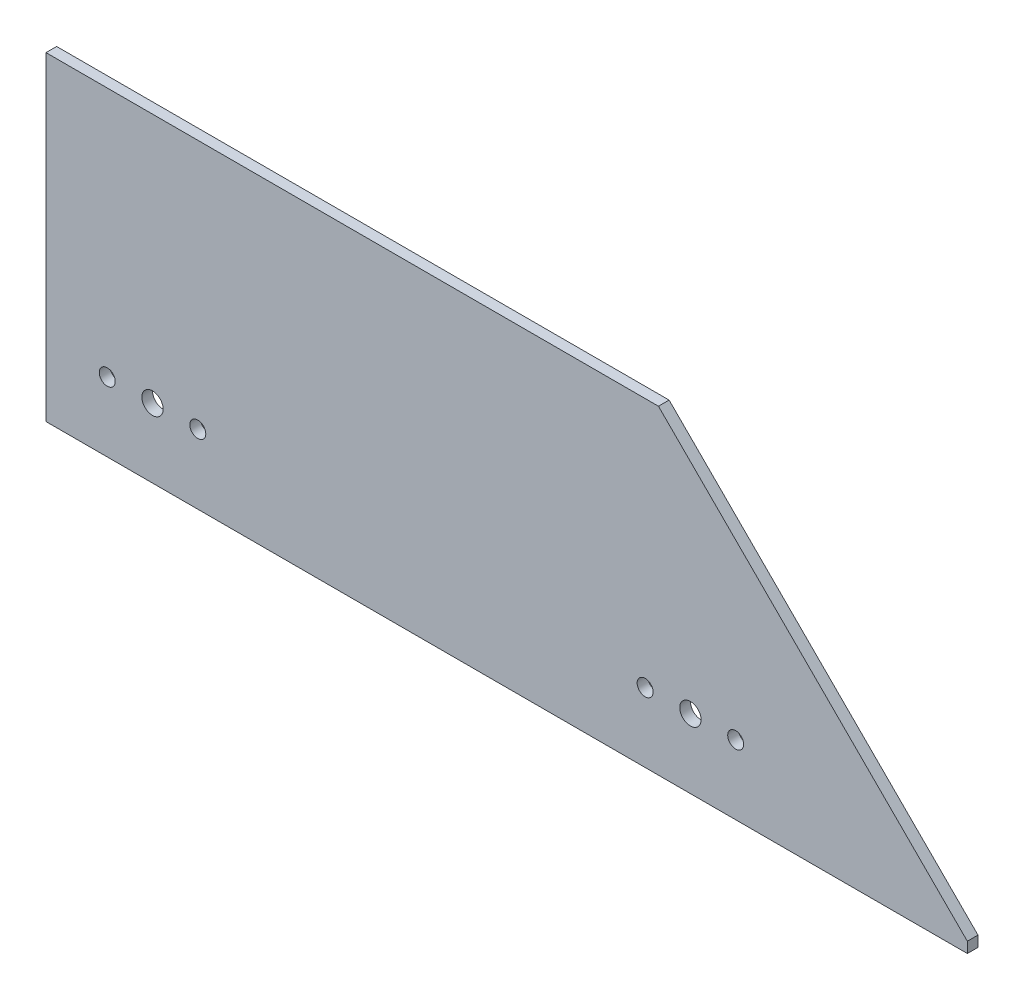
SolidWorks part; units mm, degrees
ref_plane "Front Plane" through (0, 0, 0) normal (0, 0, 1) x (1, 0, 0)
ref_plane "Top Plane" through (0, 0, 0) normal (0, 1, 0) x (1, 0, 0)
ref_plane "Right Plane" through (0, 0, 0) normal (1, 0, 0) x (0, 0, -1)
sketch "Sketch2" plane through (0, 0, 0) normal (0, 0, 1) x (1, 0, 0)
  line L0 (0, 0) -> (0, 2)
  line L2 (43, 60) -> (115, 60)
  line L4 (173, 2) -> (173, 0)
  line L5 (173, 0) -> (0, 0)
  line L8 (115, 60) -> (173, 2)
  line L9 (0, 2) -> (0, 60)
  line L10 (0, 60) -> (43, 60)
  dimension "D1" = 173
  dimension "D3" = 45
  dimension "D4" = 2
  dimension "D5" = 2
  dimension "D6" = 60
extrude "Boss-Extrude1" add sketch "Sketch2" along normal blind 2
sketch "Sketch4" plane through (0, 0, 2) normal (0, 0, 1) x (1, 0, 0)
  line L0 (0, 0) -> (173, 0) construction
  line L1 (0, 60) -> (0, 0) construction
  line L2 (173, 0) -> (173, 2) construction
  circle A0 centre (20, 13) radius 2
  circle A1 centre (121, 13) radius 2
  circle A2 centre (28.5, 13) radius 1.5
  circle A3 centre (112.5, 13) radius 1.5
  circle A4 centre (129.5, 13) radius 1.5
  circle A5 centre (11.5, 13) radius 1.5
  dimension "D1" = 4
  dimension "D2" = 4
  dimension "D4" = 3
  dimension "D9" = 8.5
  dimension "D10" = 8.5
  dimension "D3" = 13
  dimension "D5" = 20
  dimension "D6" = 52
  dimension "D7" = 8.5
  dimension "D8" = 8.5
extrude "Cut-Extrude1" cut sketch "Sketch4" against normal blind 2
